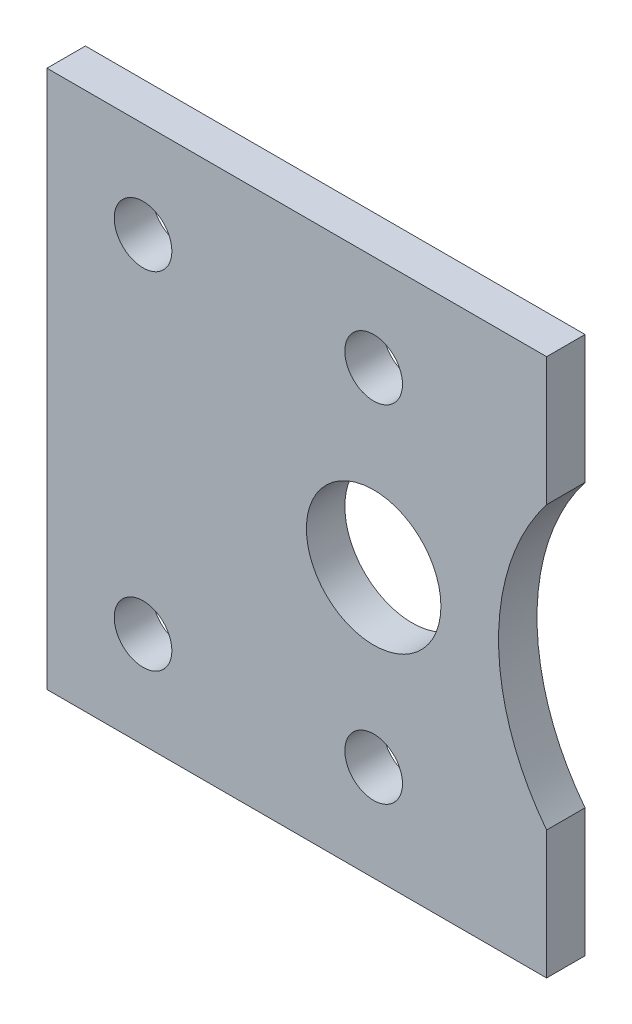
SolidWorks part; units mm, degrees
ref_plane "Front Plane" through (0, 0, 0) normal (0, 0, 1) x (1, 0, 0)
ref_plane "Top Plane" through (0, 0, 0) normal (0, 1, 0) x (1, 0, 0)
ref_plane "Right Plane" through (0, 0, 0) normal (1, 0, 0) x (0, 0, -1)
sketch "Sketch1" plane through (0, 0, 0) normal (0, 0, 1) x (1, 0, 0)
  line L0 (9, -7.3314) -> (9, -14)
  line L1 (9, -14) -> (-17, -14)
  line L2 (-17, -14) -> (-17, 14)
  line L3 (-17, 14) -> (9, 14)
  line L4 (9, 14) -> (9, 7.3314)
  line L5 (3.5, 0) -> (6.5, 0) construction
  line L6 (-17, -14) -> (-17, -9)
  line L7 (-17, -9) -> (0, -9) construction
  line L8 (-17, -9) -> (-12, -9) construction
  line L9 (-17, 0) -> (0, 0) construction
  circle A0 centre (0, 0) radius 3.5
  circle A2 centre (0, -9) radius 1.5
  circle A3 centre (-12, -9) radius 1.5
  circle A4 centre (-12, 9) radius 1.5
  circle A5 centre (0, 9) radius 1.5
  arc A6 (9, 7.3314) -> (9, -7.3314) centre (18.5, 0) ccw
  point P6 (0, 0)
  dimension "D1" = 7
  dimension "D2" = 26
  dimension "D3" = 3
  dimension "D8" = 12
  dimension "D9" = 3
  dimension "D10" = 3
  dimension "D4" = 5
  dimension "D5" = 5
  dimension "D6" = 17
  dimension "D7" = 28
extrude "Boss-Extrude1" add sketch "Sketch1" along normal blind 2
